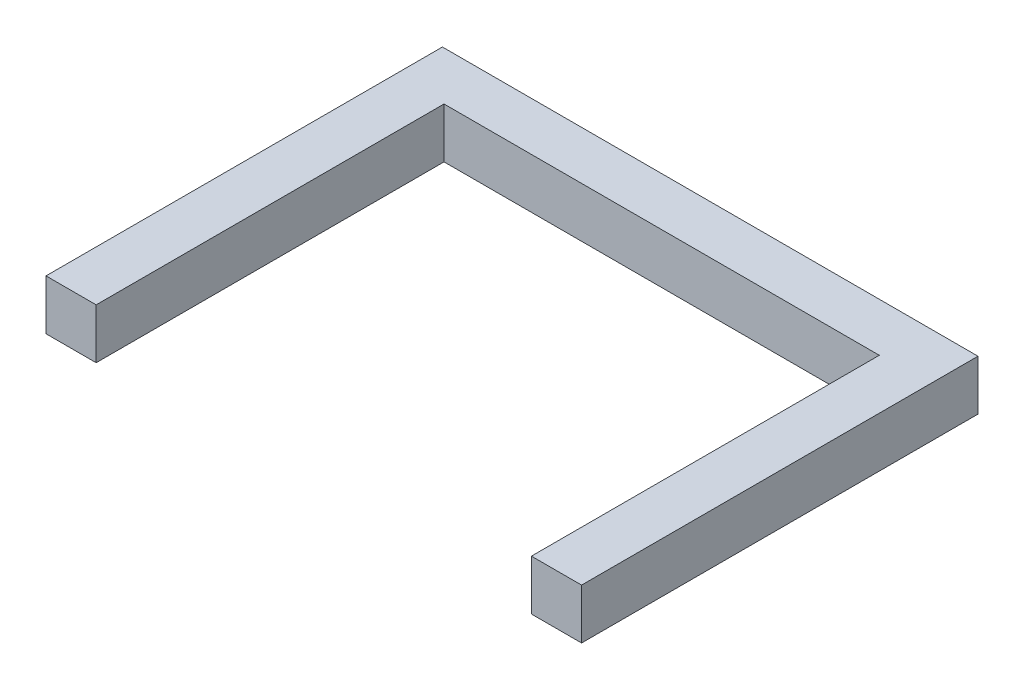
SolidWorks part; units mm, degrees
ref_plane "Front Plane" through (0, 0, 0) normal (0, 0, 1) x (1, 0, 0)
ref_plane "Top Plane" through (0, 0, 0) normal (0, 1, 0) x (1, 0, 0)
ref_plane "Right Plane" through (0, 0, 0) normal (1, 0, 0) x (0, 0, -1)
sketch "Sketch1" plane through (0, 0, 0) normal (0, 1, 0) x (1, 0, 0)
  line L0 (0, 0) -> (0, 24.5)
  line L1 (0, 24.5) -> (33.1, 24.5)
  line L2 (33.1, 24.5) -> (33.1, 0)
  line L3 (33.1, 0) -> (30, 0)
  line L4 (30, 0) -> (30, 21.5)
  line L5 (30, 21.5) -> (3.1, 21.5)
  line L6 (3.1, 21.5) -> (3.1, 0)
  line L7 (3.1, 0) -> (0, 0)
  line L8 (51.55, 1.5) -> (-18.45, 1.5) construction
  dimension "D1" = 3.1
  dimension "D2" = 33.1
  dimension "D3" = 3.1
  dimension "D4" = 3
  dimension "D5" = 20
extrude "Boss-Extrude1" add sketch "Sketch1" along normal blind 3.1
